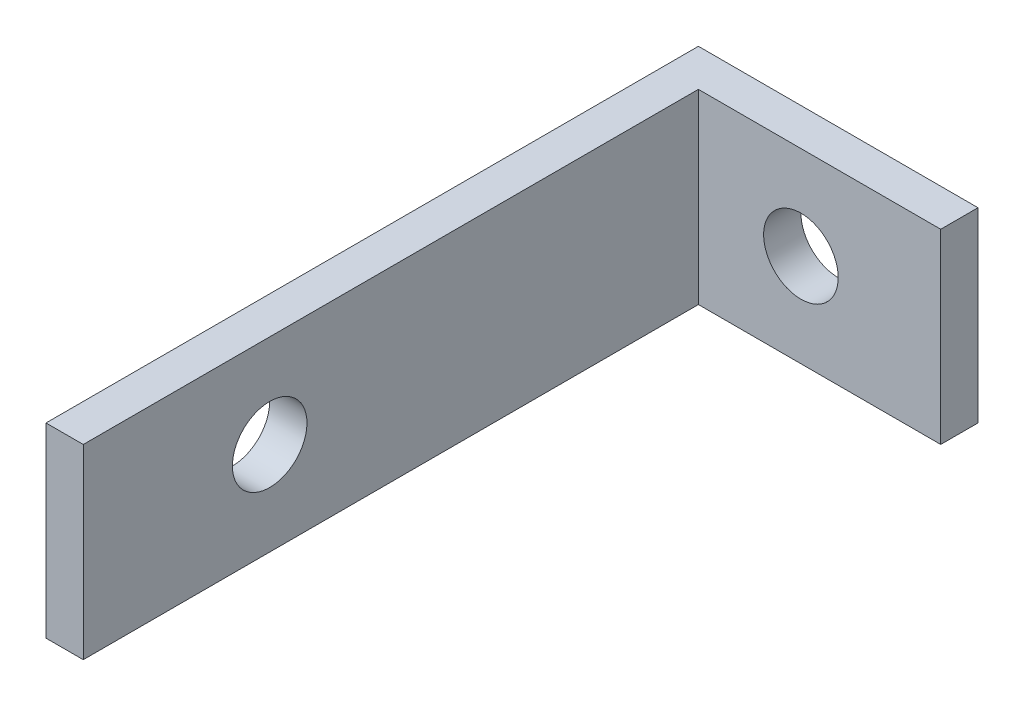
SolidWorks part; units mm, degrees
ref_plane "Front Plane" through (0, 0, 0) normal (0, 0, 1) x (1, 0, 0)
ref_plane "Top Plane" through (0, 0, 0) normal (0, 1, 0) x (1, 0, 0)
ref_plane "Right Plane" through (0, 0, 0) normal (1, 0, 0) x (0, 0, -1)
sketch "Sketch1" plane through (0, 0, 0) normal (0, 0, 1) x (1, 0, 0)
  line L1 (-7.5, 5) -> (7.5, 5)
  line L2 (-7.5, 5) -> (-7.5, -5)
  line L3 (-7.5, -5) -> (7.5, -5)
  line L4 (7.5, 5) -> (7.5, -5)
  line L5 (-7.5, 5) -> (7.5, -5) construction
  line L6 (-7.5, -5) -> (7.5, 5) construction
  point P0 (0, 0)
  dimension "D1" = 10
  dimension "D2" = 15
extrude "Boss-Extrude2" add sketch "Sketch1" along normal blind 2
sketch "Sketch2" plane through (0, 0, 2) normal (0, 0, 1) x (1, 0, 0)
  circle A0 centre (0, 0) radius 2
  dimension "D1" = 4
extrude "Cut-Extrude2" cut sketch "Sketch2" against normal blind 2
sketch "Sketch3" plane through (0, 0, 2) normal (0, 0, 1) x (1, 0, 0)
  line L0 (-7.5, -5) -> (7.5, -5) construction
  line L1 (-7.5, 5) -> (-5.5, 5)
  line L2 (-7.5, 5) -> (-7.5, -5)
  line L3 (-7.5, -5) -> (-5.5, -5)
  line L4 (-5.5, 5) -> (-5.5, -5)
  dimension "D1" = 2
extrude "Boss-Extrude3" add sketch "Sketch3" along normal blind 33
sketch "Sketch4" plane through (-5.5, 0, 0) normal (1, 0, 0) x (0, 0, -1)
  line L0 (0, -5) -> (0, 5) construction
  line L1 (-35, 5) -> (-2, 5) construction
  circle A0 centre (-25, 0) radius 2
  dimension "D1" = 4
  dimension "D2" = 25
  dimension "D3" = 5
extrude "Cut-Extrude3" cut sketch "Sketch4" against normal blind 33
